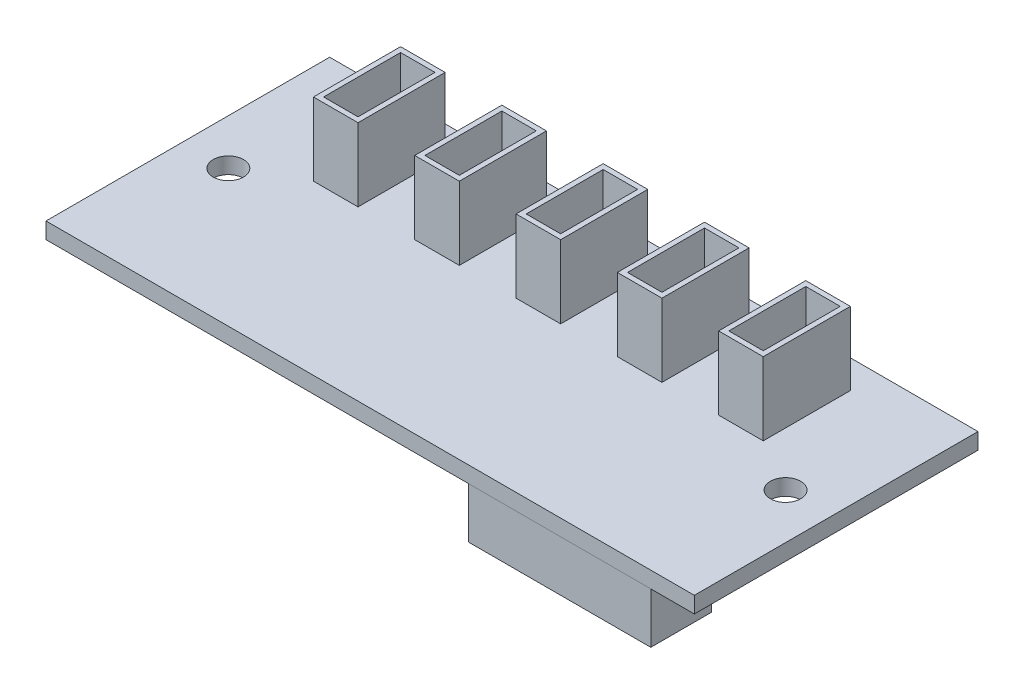
SolidWorks part; units mm, degrees
ref_plane "Front Plane" through (0, 0, 0) normal (0, 0, 1) x (1, 0, 0)
ref_plane "Top Plane" through (0, 0, 0) normal (0, 1, 0) x (1, 0, 0)
ref_plane "Right Plane" through (0, 0, 0) normal (1, 0, 0) x (0, 0, -1)
sketch "Sketch1" plane through (0, 0, 0) normal (0, 1, 0) x (1, 0, 0)
  line L0 (-32, -0.5) -> (-27.5, -0.5) construction
  line L1 (32, 14) -> (-32, 14)
  line L2 (32, 14) -> (32, -14)
  line L3 (32, -14) -> (-32, -14)
  line L4 (-32, 14) -> (-32, -14)
  line L5 (32, 14) -> (-32, -14) construction
  line L6 (32, -14) -> (-32, 14) construction
  line L7 (-27.5, -0.5) -> (27.5, -0.5) construction
  line L8 (27.5, -0.5) -> (32, -0.5) construction
  circle A0 centre (-27.5, -0.5) radius 1.5
  circle A1 centre (27.5, -0.5) radius 1.5
  point P0 (0, 0)
  dimension "D3" = 3
  dimension "D1" = 64
  dimension "D2" = 28
  dimension "D4" = 55
  dimension "D5" = 14.5
extrude "Boss-Extrude1" add sketch "Sketch1" along normal blind 1.6 contours L1 L4 L3 L2 A1 A0
sketch "Sketch2" plane through (0, 1.6, 0) normal (0, 1, 0) x (1, 0, 0)
  line L0 (32, 14) -> (-32, 14) construction
  line L1 (2.2, 11.2) -> (-2.2, 11.2)
  line L2 (2.2, 11.2) -> (2.2, 2.6)
  line L3 (2.2, 2.6) -> (-2.2, 2.6)
  line L4 (-2.2, 11.2) -> (-2.2, 2.6)
  line L5 (12.2, 11.2) -> (12.2, 2.6)
  line L6 (12.2, 11.2) -> (7.8, 11.2)
  line L7 (7.8, 11.2) -> (7.8, 2.6)
  line L8 (12.2, 2.6) -> (7.8, 2.6)
  line L9 (22.2, 11.2) -> (22.2, 2.6)
  line L10 (22.2, 11.2) -> (17.8, 11.2)
  line L11 (17.8, 11.2) -> (17.8, 2.6)
  line L12 (22.2, 2.6) -> (17.8, 2.6)
  line L13 (2.2, 11.2) -> (12.2, 11.2) construction
  line L14 (-7.8, 11.2) -> (-7.8, 2.6)
  line L15 (-7.8, 11.2) -> (-12.2, 11.2)
  line L16 (-12.2, 11.2) -> (-12.2, 2.6)
  line L17 (-7.8, 2.6) -> (-12.2, 2.6)
  line L18 (-17.8, 11.2) -> (-17.8, 2.6)
  line L19 (-17.8, 11.2) -> (-22.2, 11.2)
  line L20 (-22.2, 11.2) -> (-22.2, 2.6)
  line L21 (-17.8, 2.6) -> (-22.2, 2.6)
  line L22 (2.2, 11.2) -> (-7.8, 11.2) construction
  point P6 (0, 14)
  point P7 (0, 11.2)
  dimension "D1" = 8.6
  dimension "D2" = 4.4
  dimension "D3" = 2.8
  dimension "D5" = 10
  dimension "D7" = 10
  dimension "D4" = 3
  dimension "D6" = 3
extrude "Boss-Extrude2" add sketch "Sketch2" along normal blind 7.2 separate body
shell "Shell1" thickness 0.5
shell "Shell2" thickness 0.5
shell "Shell3" thickness 0.5
shell "Shell4" thickness 0.5
shell "Shell5" thickness 0.5
sketch "Sketch3" plane through (0, 0, 0) normal (0, -1, 0) x (1, 0, 0)
  line L0 (32, 14) -> (-32, 14) construction
  line L1 (27.7, 14) -> (9.7, 14)
  line L2 (27.7, 14) -> (27.7, 8)
  line L3 (27.7, 8) -> (9.7, 8)
  line L4 (9.7, 14) -> (9.7, 8)
  line L5 (32, -14) -> (32, 14) construction
  dimension "D1" = 18
  dimension "D2" = 6
  dimension "D3" = 4.3
extrude "Boss-Extrude3" add sketch "Sketch3" along normal blind 5 separate body
equation "\"drill\"=0.3"
equation "\"D3@Sketch1\"=\"drill\""
